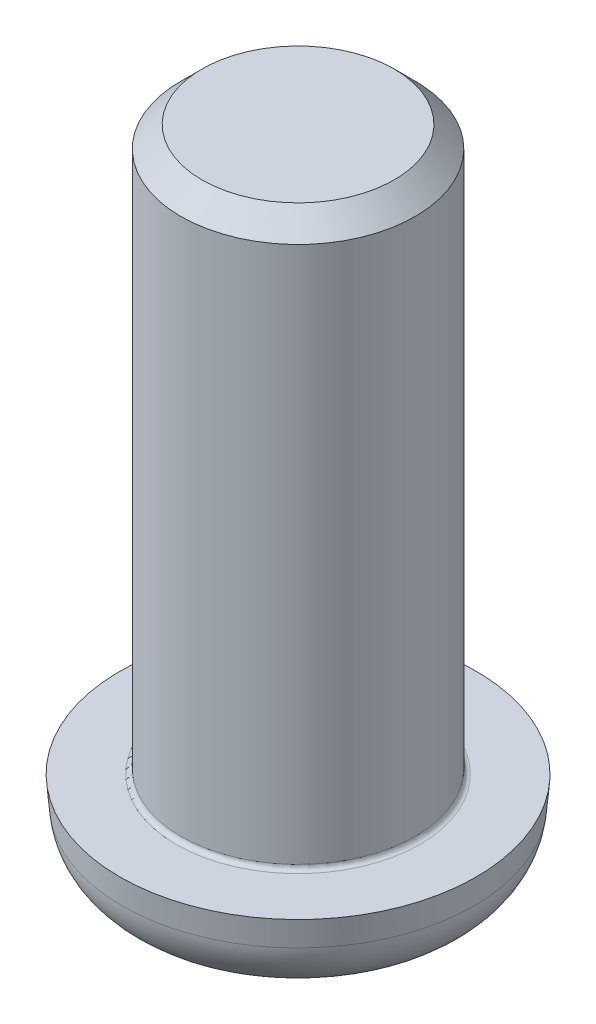
SolidWorks part; units mm, degrees
ref_plane "Front" through (0, 0, 0) normal (0, 0, 1) x (1, 0, 0)
ref_plane "Top" through (0, 0, 0) normal (0, 1, 0) x (1, 0, 0)
ref_plane "Right" through (0, 0, 0) normal (1, 0, 0) x (0, 0, -1)
sketch "Sketch1" plane through (0, 0, 0) normal (1, 0, 0) x (0, 0, -1)
  line L0 (0, 0) -> (0, 1.235) construction
  line L1 (-1.25, 0) -> (-1.25, 6)
  line L2 (-1.25, 6) -> (0, 6)
  line L3 (0, 6) -> (0, -0.8)
  line L4 (0, -0.8) -> (-1.52, -0.8)
  line L5 (-1.25, 0) -> (-1.9, 0)
  line L6 (-1.9, 0) -> (-1.8755, -0.28)
  line L7 (0, 0) -> (-1.25, 0) construction
  line L8 (-1.9, 0) -> (-1.9, -1.0829) construction
  arc A0 (-1.8755, -0.28) -> (-1.52, -0.8) centre (-1.2356, -0.224) ccw
  dimension "d" = 2.5
  dimension "H" = 0.8
  dimension "D1" = 3.04
  dimension "DD" = 3.8
  dimension "D2" = 5
  dimension "D3" = 0.52
  dimension "L" = 6
revolve "Revolve1" add sketch "Sketch1" angle 360 about L3
fillet "Fillet5" radius 0.2 1 edges at (0, -0.8, 1.52)
sketch "Sketch2" plane through (0, -0.8, 0) normal (0, -1, 0) x (1, 0, 0)
  line L0 (-2.0062, 0) -> (2.7281, 0) construction
  line L1 (0, 2.3126) -> (0, -2.1951) construction
  line L2 (0.1785, 0.1785) -> (1.05, 0.1785)
  line L3 (-0.1785, 1.05) -> (0.1785, 1.05)
  line L4 (-0.1785, 1.05) -> (-0.1785, 0.1785)
  line L5 (-0.1785, -1.05) -> (0.1785, -1.05)
  line L6 (0.1785, 1.05) -> (0.1785, 0.1785)
  line L7 (-1.05, 0.1785) -> (-0.1785, 0.1785)
  line L8 (-1.05, 0.1785) -> (-1.05, -0.1785)
  line L9 (-1.05, -0.1785) -> (-0.1785, -0.1785)
  line L10 (1.05, 0.1785) -> (1.05, -0.1785)
  line L11 (-0.1785, -0.1785) -> (-0.1785, -1.05)
  line L12 (0.1785, -0.1785) -> (1.05, -0.1785)
  line L13 (0.1785, -0.1785) -> (0.1785, -1.05)
  line L14 (-0.1785, -1.05) -> (-0.1785, -1.5) construction
  dimension "M" = 2.1
  dimension "D2" = 2.1
  dimension "D3" = 0.357
  dimension "p" = 0.45
extrude "Cut-Extrude1" cut sketch "Sketch2" against normal blind 1.52 draft 2
fillet "Fillet4" radius 0.05 1 edges at (0, 0, 1.25)
chamfer "Chamfer1" distance 0.225 angle 45 1 edges at (0, 6, 1.25)
other "Freeze***"
equation "\"D2@Sketch2\" = \"M@Sketch2\""
equation "\"D3@Sketch2\" = \"M@Sketch2\" * 0.17"
equation "\"D1@Sketch1\" = \"DD@Sketch1\" * 0.8"
equation "\"D3@Sketch1\" = \"H@Sketch1\" * 0.65"
equation "\"D1@Chamfer1\" = \"p@Sketch2\" / 2"
